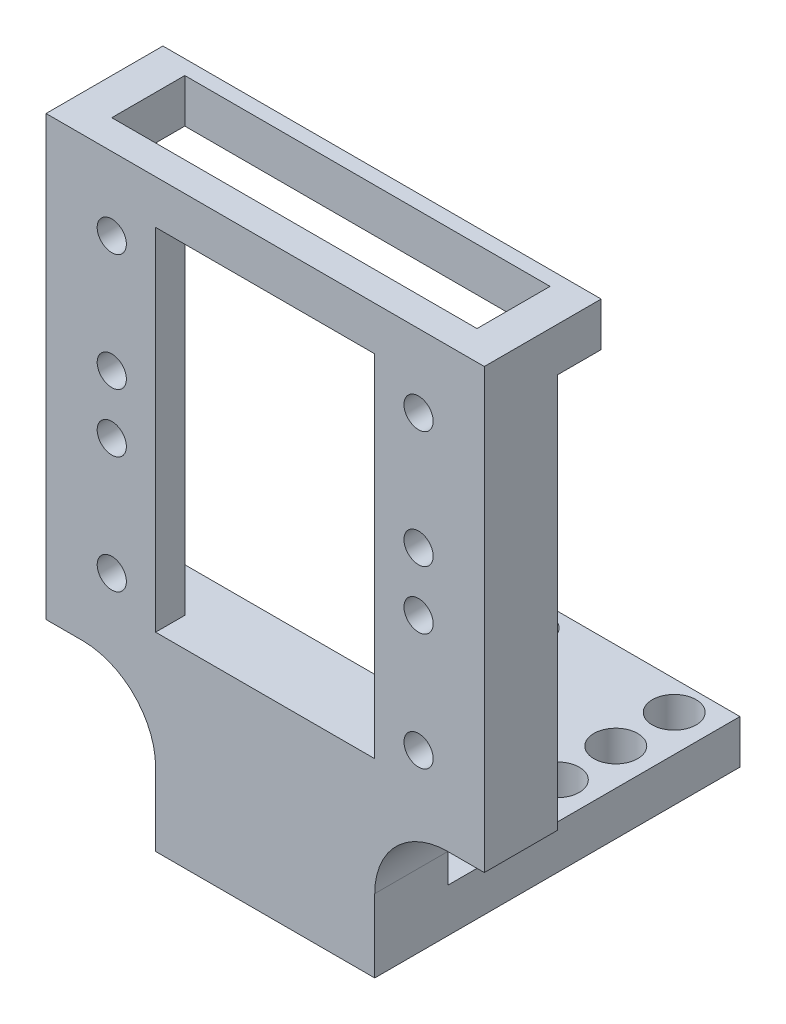
SolidWorks part; units mm, degrees
ref_plane "Front Plane" through (0, 0, 0) normal (0, 0, 1) x (1, 0, 0)
ref_plane "Top Plane" through (0, 0, 0) normal (0, 1, 0) x (1, 0, 0)
ref_plane "Right Plane" through (0, 0, 0) normal (1, 0, 0) x (0, 0, -1)
sketch "Sketch1" plane through (0, 0, 0) normal (0, 0, 1) x (1, 0, 0)
  line L1 (-15, 15) -> (15, 15)
  line L2 (-15, 15) -> (-15, -15)
  line L3 (-15, -15) -> (15, -15)
  line L4 (15, 15) -> (15, -15)
  line L5 (-15, 15) -> (15, -15) construction
  line L6 (-15, -15) -> (15, 15) construction
  point P0 (0, 0)
  dimension "D1" = 30
  dimension "D2" = 30
extrude "Boss-Extrude1" add sketch "Sketch1" along normal blind 5
sketch "Sketch2" plane through (0, 0, 0) normal (0, 0, -1) x (-1, 0, 0)
  line L1 (12.5, 12) -> (-12.5, 12)
  line L2 (12.5, 12) -> (12.5, -12)
  line L3 (12.5, -12) -> (-12.5, -12)
  line L4 (-12.5, 12) -> (-12.5, -12)
  point P0 (0, 12)
  point P1 (12.5, 12)
  point P3 (-12.5, 12)
  point P4 (-12.5, -12)
  dimension "D1" = 12
  dimension "D2" = 12.5
  dimension "D3" = 25
  dimension "D4" = 24
extrude "Cut-Extrude1" cut sketch "Sketch2" against normal blind 3
sketch "Sketch3" plane through (0, 0, 3) normal (0, 0, -1) x (-1, 0, 0)
  line L0 (12.5, 12) -> (-12.5, 12) construction
  line L1 (-12.5, -12) -> (12.5, -12) construction
  line L2 (-7.5, 12) -> (7.5, 12)
  line L3 (-7.5, 12) -> (-7.5, -12)
  line L4 (-7.5, -12) -> (7.5, -12)
  line L5 (7.5, 12) -> (7.5, -12)
  point P0 (-7.5, 12)
  point P1 (7.5, 12)
  dimension "D1" = 5
  dimension "D2" = 5
extrude "Cut-Extrude2" cut sketch "Sketch3" against normal through all
sketch "Sketch4" plane through (0, 0, 3) normal (0, 0, -1) x (-1, 0, 0)
  line L0 (12.5, 12) -> (7.5, 12) construction
  line L1 (12.5, -12) -> (12.5, 12) construction
  line L2 (7.5, -12) -> (12.5, -12) construction
  line L3 (-12.5, 12) -> (-12.5, -12) construction
  line L4 (-7.5, 12) -> (-12.5, 12) construction
  line L5 (-12.5, -12) -> (-7.5, -12) construction
  circle A0 centre (10.5, 10) radius 1
  circle A1 centre (10.5, -10) radius 1
  circle A2 centre (-10.5, 10) radius 1
  circle A3 centre (-10.5, -10) radius 1
  point P0 (10.5, 10)
  point P1 (10.5, -10)
  point P2 (-10.5, -10)
  point P3 (-10.5, 10)
  dimension "D9" = 2
  dimension "D10" = 2
  dimension "D11" = 2
  dimension "D12" = 2
  dimension "D1" = 2
  dimension "D2" = 2
  dimension "D3" = 2
  dimension "D4" = 2
  dimension "D5" = 2
  dimension "D6" = 2
  dimension "D7" = 2
  dimension "D8" = 2
extrude "Cut-Extrude3" cut sketch "Sketch4" against normal through all
sketch "Sketch5" plane through (0, 0, 0) normal (0, 0, -1) x (-1, 0, 0)
  line L0 (15, 15) -> (15, -15) construction
  line L1 (-15, 15) -> (15, 15)
  line L2 (-15, 15) -> (-15, 12)
  line L3 (-15, 12) -> (15, 12)
  line L4 (15, 15) -> (15, 12)
  line L5 (-15, -15) -> (-15, 15) construction
  line L6 (-15, -15) -> (15, -15)
  line L7 (-15, -15) -> (-15, -12)
  line L8 (-15, -12) -> (15, -12)
  line L9 (15, -15) -> (15, -12)
  line L10 (15, -15) -> (-15, -15) construction
  dimension "D1" = 3
  dimension "D2" = 3
extrude "Boss-Extrude2" add sketch "Sketch5" along normal blind 3
sketch "Sketch6" plane through (0, 0, 3) normal (0, 0, -1) x (-1, 0, 0)
  line L0 (12.5, -12) -> (12.5, 12) construction
  line L1 (-12.5, 12) -> (-12.5, -12) construction
  line L2 (12.5, 12) -> (7.5, 12) construction
  line L3 (7.5, -12) -> (12.5, -12) construction
  line L4 (-7.5, 12) -> (-12.5, 12) construction
  line L5 (-12.5, -12) -> (-7.5, -12) construction
  circle A0 centre (-10.5, 2) radius 1
  circle A1 centre (-10.5, -2) radius 1
  circle A2 centre (10.5, 2) radius 1
  circle A3 centre (10.5, -2) radius 1
  point P0 (10.5, -2)
  point P1 (10.5, 2)
  point P2 (-10.5, -2)
  point P3 (-10.5, 2)
  dimension "D9" = 2
  dimension "D10" = 2
  dimension "D11" = 2
  dimension "D12" = 2
  dimension "D1" = 2
  dimension "D2" = 2
  dimension "D3" = 2
  dimension "D4" = 2
  dimension "D5" = 14
  dimension "D6" = 14
  dimension "D7" = 14
  dimension "D8" = 14
extrude "Cut-Extrude4" cut sketch "Sketch6" against normal through all
sketch "Sketch7" plane through (0, 15, 0) normal (0, 1, 0) x (1, 0, 0)
  line L0 (15, -5) -> (15, 3) construction
  line L1 (15, -5) -> (-15, -5) construction
  line L2 (-15, -5) -> (-15, 3) construction
  line L3 (-15, 3) -> (15, 3) construction
  line L5 (12.5, -3) -> (-12.5, -3)
  line L6 (12.5, -3) -> (12.5, 2)
  line L7 (12.5, 2) -> (-12.5, 2)
  line L8 (-12.5, -3) -> (-12.5, 2)
  point P0 (12.5, -3)
  point P5 (-12.5, -3)
  point P8 (-12.5, 2)
  dimension "D1" = 2.5
  dimension "D2" = 2
  dimension "D3" = 2
  dimension "D4" = 2.5
  dimension "D5" = 1
extrude "Cut-Extrude5" cut sketch "Sketch7" against normal blind 4
sketch "Sketch8" plane through (0, 0, -3) normal (0, 0, -1) x (-1, 0, 0)
  line L1 (-15, -12) -> (15, -12)
  line L2 (-15, -12) -> (-15, -15)
  line L3 (-15, -15) -> (15, -15)
  line L4 (15, -12) -> (15, -15)
extrude "Cut-Extrude7" cut sketch "Sketch8" against normal blind 3
sketch "Sketch9" plane through (0, -15, 0) normal (0, -1, 0) x (1, 0, 0)
  line L1 (15, 0) -> (-15, 0)
  line L2 (15, 0) -> (15, 5)
  line L3 (15, 5) -> (-15, 5)
  line L4 (-15, 0) -> (-15, 5)
extrude "Boss-Extrude3" add sketch "Sketch9" along normal blind 10
sketch "Sketch12" plane through (0, 0, 0) normal (0, 0, -1) x (-1, 0, 0)
  line L0 (15, -25) -> (-15, -25) construction
  line L2 (-7.5, -25) -> (7.5, -25)
  line L3 (-7.5, -25) -> (-7.5, -22)
  line L4 (-7.5, -22) -> (7.5, -22)
  line L5 (7.5, -25) -> (7.5, -22)
  point P0 (0, -25)
  point P1 (7.5, -25)
  point P4 (-7.5, -25)
  dimension "D1" = 7.5
  dimension "D2" = 7.5
  dimension "D3" = 3
extrude "Boss-Extrude5" add sketch "Sketch12" along normal blind 20
sketch "Sketch13" plane through (0, 0, 0) normal (0, 0, -1) x (-1, 0, 0)
  line L1 (-15, -25) -> (-7.5, -25)
  line L2 (-15, -25) -> (-15, -15)
  line L3 (-15, -15) -> (-7.5, -15)
  line L4 (-7.5, -25) -> (-7.5, -15)
  line L5 (15, -25) -> (7.5, -25)
  line L6 (15, -25) -> (15, -15)
  line L7 (15, -15) -> (7.5, -15)
  line L8 (7.5, -25) -> (7.5, -15)
  dimension "D1" = 10
  dimension "D2" = 10
  dimension "D3" = 7.5
  dimension "D4" = 7.5
extrude "Cut-Extrude9" cut sketch "Sketch13" against normal through all
sketch "Sketch14" plane through (0, -22, 0) normal (0, 1, 0) x (1, 0, 0)
  line L0 (-7.5, 20) -> (-7.5, 0) construction
  line L1 (7.5, 20) -> (7.5, 0) construction
  circle A0 centre (-5, 6) radius 1.5
  circle A1 centre (-5, 10) radius 1.5
  circle A2 centre (-5, 14) radius 1.5
  circle A3 centre (-5, 18) radius 1.5
  circle A4 centre (5, 6) radius 1.5
  circle A5 centre (5, 10) radius 1.5
  circle A6 centre (5, 14) radius 1.5
  circle A7 centre (5, 18) radius 1.5
  point P0 (-7.5, 10)
  point P1 (7.5, 10)
  point P4 (-5, 10)
  point P7 (5, 10)
  point P8 (-5, 14)
  point P9 (-5, 6)
  point P10 (-5, 18)
  point P11 (5, 14)
  point P12 (5, 18)
  point P13 (5, 6)
  dimension "D6" = 3
  dimension "D7" = 3
  dimension "D8" = 3
  dimension "D9" = 3
  dimension "D10" = 3
  dimension "D11" = 3
  dimension "D12" = 3
  dimension "D13" = 3
  dimension "D1" = 2.5
  dimension "D2" = 2.5
  dimension "D3" = 4
  dimension "D4" = 4
  dimension "D5" = 4
extrude "Cut-Extrude10" cut sketch "Sketch14" against normal through all
fillet "Fillet1" radius 5 1 edges at (7.5, -15, 2.5)
fillet "Fillet2" radius 5 1 edges at (-7.5, -15, 2.5)
